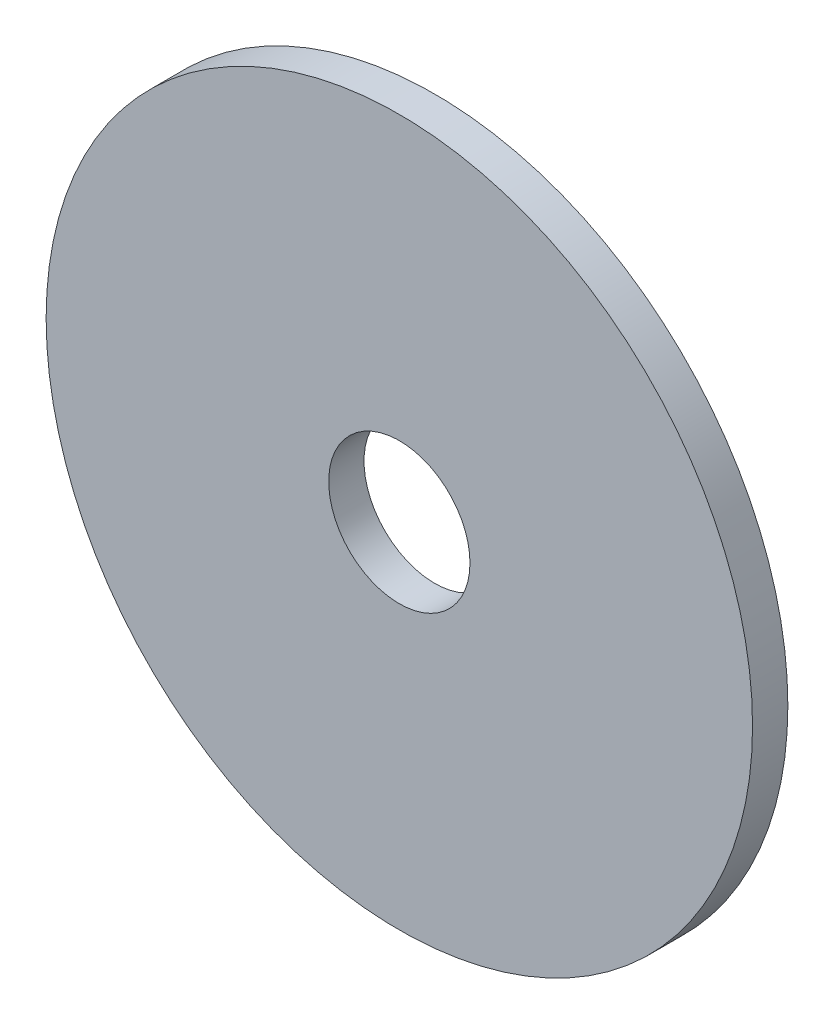
SolidWorks part; units mm, degrees
ref_plane "Front Plane" through (0, 0, 0) normal (0, 0, 1) x (1, 0, 0)
ref_plane "Top Plane" through (0, 0, 0) normal (0, 1, 0) x (1, 0, 0)
ref_plane "Right Plane" through (0, 0, 0) normal (1, 0, 0) x (0, 0, -1)
sketch "Sketch1" plane through (0, 0, 0) normal (0, 0, 1) x (1, 0, 0)
  circle A0 centre (0, 0) radius 50
  circle A1 centre (0, 0) radius 10
  dimension "D1" = 100
  dimension "D2" = 20
extrude "Boss-Extrude1" add sketch "Sketch1" along normal blind 5
